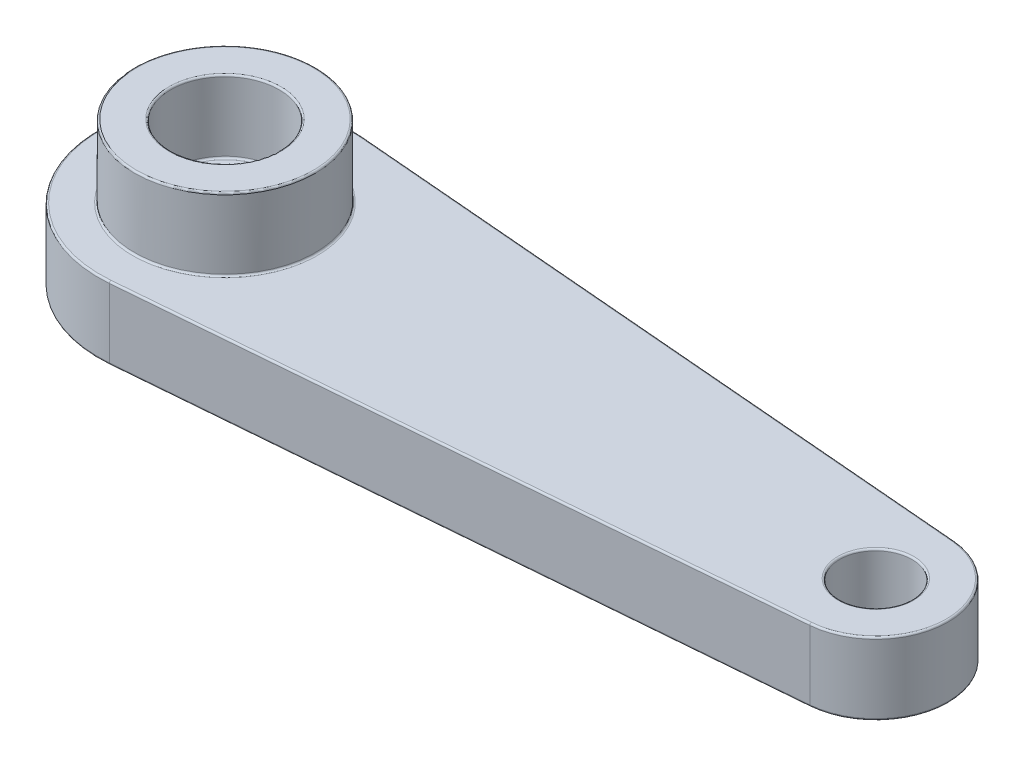
SolidWorks part; units mm, degrees
ref_plane "Front Plane" through (0, 0, 0) normal (0, 0, 1) x (1, 0, 0)
ref_plane "Top Plane" through (0, 0, 0) normal (0, 1, 0) x (1, 0, 0)
ref_plane "Right Plane" through (0, 0, 0) normal (1, 0, 0) x (0, 0, -1)
sketch "Sketch1" plane through (0, 0, 0) normal (0, 1, 0) x (1, 0, 0)
  circle A0 centre (0, 0) radius 1.5
  circle A1 centre (0, 0) radius 2.5
  dimension "D1" = 3
  dimension "D2" = 1
extrude "Boss-Extrude1" add sketch "Sketch1" along normal blind 2
sketch "Sketch2" plane through (0, 0, 0) normal (0, 1, 0) x (1, 0, 0)
  line L0 (0.2917, 3.4878) -> (18.1667, 1.993)
  line L1 (0.2917, -3.4878) -> (18.1667, -1.993)
  circle A0 centre (18, 0) radius 1
  circle A1 centre (0, 0) radius 0.5
  arc A2 (0.2917, -3.4878) -> (0.2917, 3.4878) centre (0, 0) cw
  arc A3 (18.1667, 1.993) -> (18.1667, -1.993) centre (18, 0) cw
  point P6 (18.0613, 0.7758)
  dimension "D1" = 2
  dimension "D2" = 2
  dimension "D3" = 1
  dimension "D4" = 3.5
  dimension "D5" = 18
extrude "Boss-Extrude2" add sketch "Sketch2" against normal blind 2
sketch "Sketch3" plane through (0, -2, 0) normal (0, -1, 0) x (1, 0, 0)
  circle A0 centre (0, 0) radius 0.5 construction
  circle A1 centre (0, 0) radius 0.5
  circle A2 centre (0, 0) radius 2
  dimension "D1" = 1.5
extrude "Cut-Extrude1" cut sketch "Sketch3" against normal blind 0.5
fillet "Fillet1" radius 0.05 18 edges at (0, -1.5, -0.5) (0, -2, -2) (0, -1.5, -2) (0, 0, 0.5) (18, 0, 1) (18, -2, 1) (-3.5, 0, 0) (9.2292, 0, 2.7404) (20, 0, 0) (9.2292, 0, -2.7404) (-3.5, -2, 0) (9.2292, -2, 2.7404) (20, -2, 0) (0, 0, 2.5) (0, 0, 1.5) (0, 2, 1.5) (0, 2, 2.5) (9.2292, -2, -2.7404)
